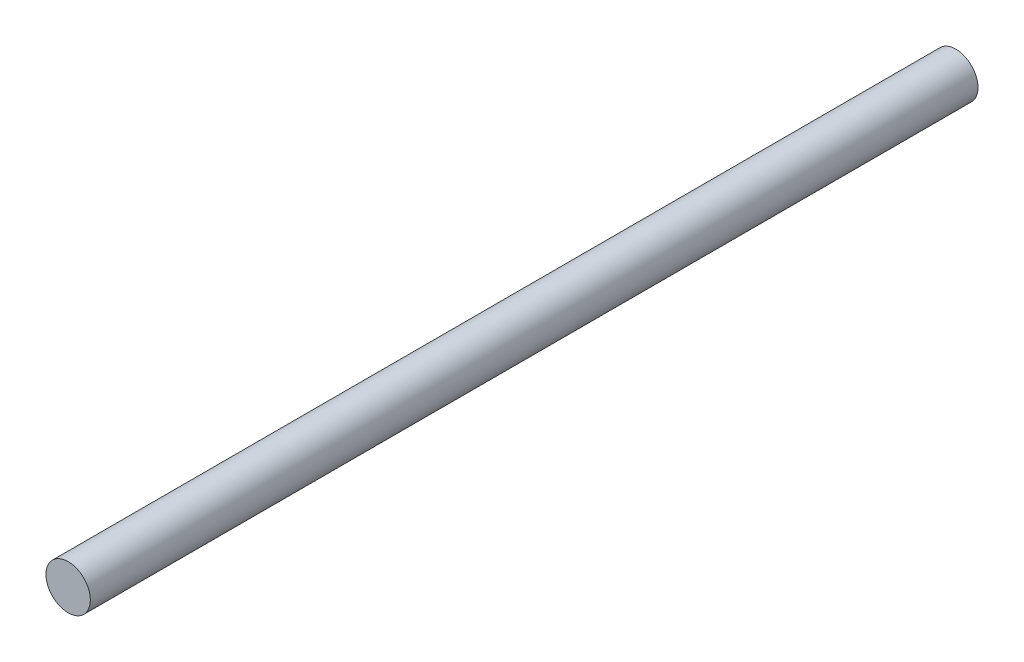
SolidWorks part; units mm, degrees
ref_plane "Front Plane" through (0, 0, 0) normal (0, 0, 1) x (1, 0, 0)
ref_plane "Top Plane" through (0, 0, 0) normal (0, 1, 0) x (1, 0, 0)
ref_plane "Right Plane" through (0, 0, 0) normal (1, 0, 0) x (0, 0, -1)
sketch "Sketch1" plane through (0, 0, 0) normal (0, 0, 1) x (1, 0, 0)
  circle A0 centre (0, 0) radius 3.175
extrude "Boss-Extrude1" add sketch "Sketch1" along normal blind 127
